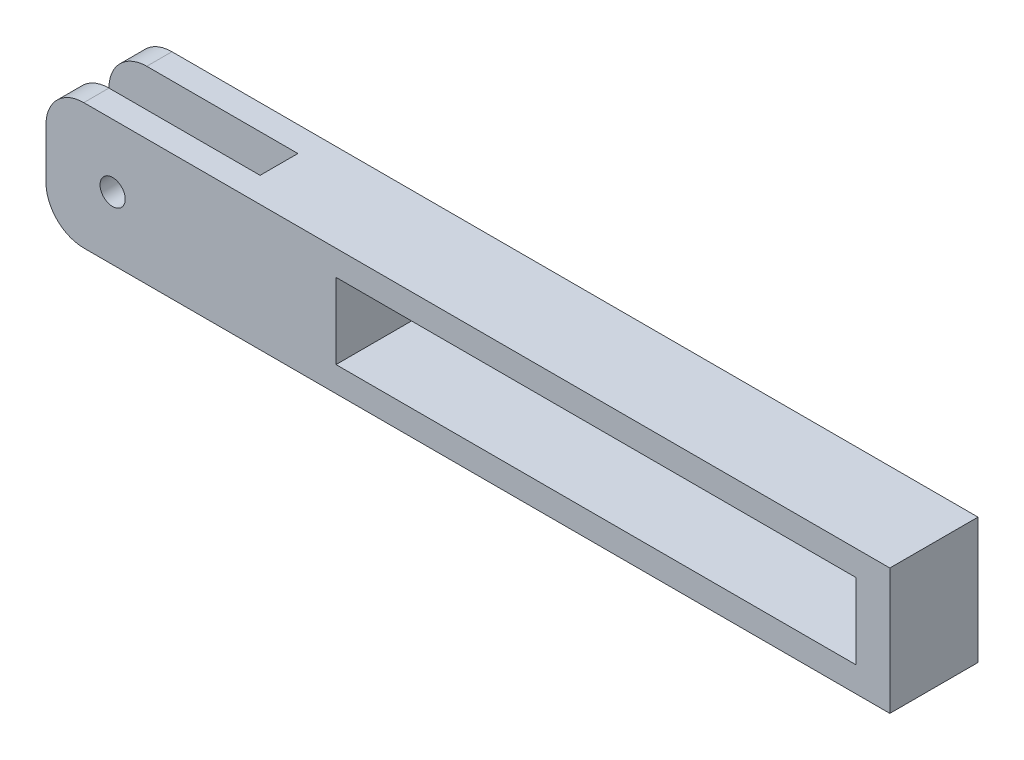
SolidWorks part; units mm, degrees
ref_plane "Front Plane" through (0, 0, 0) normal (0, 0, 1) x (1, 0, 0)
ref_plane "Top Plane" through (0, 0, 0) normal (0, 1, 0) x (1, 0, 0)
ref_plane "Right Plane" through (0, 0, 0) normal (1, 0, 0) x (0, 0, -1)
sketch "Sketch3" plane through (0, 0, 0) normal (0, 0, 1) x (1, 0, 0)
  line L0 (0, 135.4373) -> (0, -172.6431) construction
  line L1 (-52.3664, -15) -> (154.0175, -15)
  line L2 (-167.5, 10) -> (-167.5, -10)
  line L3 (-152.5, -25) -> (167.5, -25)
  line L4 (167.5, -25) -> (167.5, 25)
  line L5 (167.5, 25) -> (-152.5, 25)
  line L6 (154.0175, 15) -> (154.0175, -15)
  line L7 (-84.8154, 0) -> (27.9493, 0) construction
  line L8 (-52.3664, -15) -> (-52.3664, 15)
  line L9 (-52.3664, 15) -> (154.0175, 15)
  arc A0 (-167.5, -10) -> (-152.5, -25) centre (-152.5, -10) ccw
  arc A1 (-152.5, 25) -> (-167.5, 10) centre (-152.5, 10) ccw
  point P12 (-167.5, -25)
  dimension "D3" = 15
  dimension "D1" = 335
  dimension "D2" = 167.5
  dimension "D4" = 50
  dimension "D5" = 15
  dimension "D6" = 30
  dimension "D7" = 30
extrude "Boss-Extrude1" add sketch "Sketch3" along normal blind 35
sketch "Sketch5" plane through (0, -25, 0) normal (0, -1, 0) x (1, 0, 0)
  line L0 (-167.5, 17.5) -> (-34.72, 17.5) construction
  line L1 (-167.5, 35) -> (-167.5, 0) construction
  line L2 (-167.5, 25) -> (-92.5, 25)
  line L3 (-92.5, 25) -> (-92.5, 10)
  line L4 (-92.5, 10) -> (-167.5, 10)
  line L5 (-167.5, 25) -> (-167.5, 10)
  dimension "D1" = 15
  dimension "D2" = 7.5
  dimension "D3" = 75
extrude "Cut-Extrude2" cut sketch "Sketch5" against normal up to next
sketch "Sketch6" plane through (0, 0, 0) normal (0, 0, -1) x (-1, 0, 0)
  circle A0 centre (141.0502, 0) radius 5
  dimension "D1" = 10
extrude "Cut-Extrude3" cut sketch "Sketch6" against normal through all
